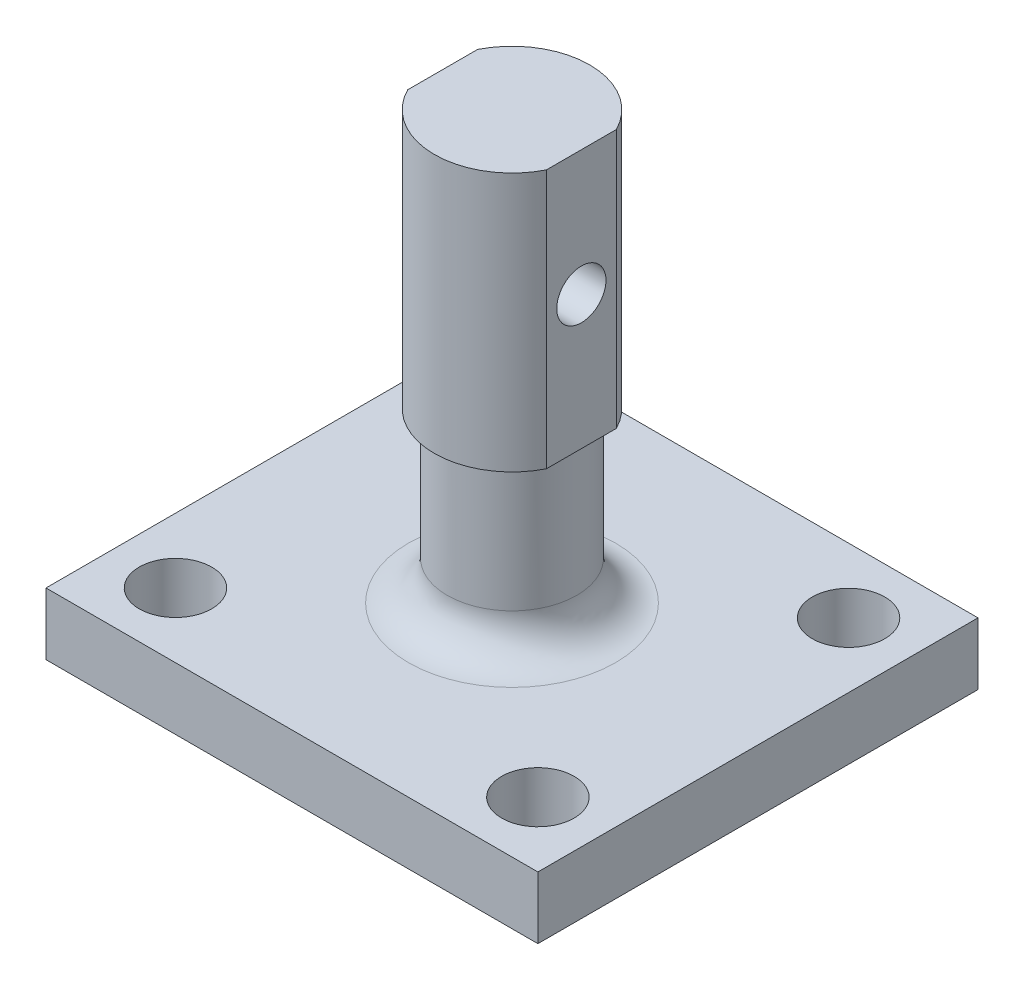
SolidWorks part; units mm, degrees
ref_plane "Front Plane" through (0, 0, 0) normal (0, 0, 1) x (1, 0, 0)
ref_plane "Top Plane" through (0, 0, 0) normal (0, 1, 0) x (1, 0, 0)
ref_plane "Right Plane" through (0, 0, 0) normal (1, 0, 0) x (0, 0, -1)
sketch "Sketch1" plane through (0, 0, 0) normal (0, 1, 0) x (1, 0, 0)
  line L1 (-4.75, 4.25) -> (4.75, 4.25)
  line L2 (-4.75, 4.25) -> (-4.75, -4.25)
  line L3 (-4.75, -4.25) -> (4.75, -4.25)
  line L4 (4.75, 4.25) -> (4.75, -4.25)
  line L5 (-4.75, 4.25) -> (4.75, -4.25) construction
  line L6 (-4.75, -4.25) -> (4.75, 4.25) construction
  point P0 (0, 0)
  dimension "D1" = 8.5
  dimension "D2" = 9.5
extrude "Boss-Extrude1" add sketch "Sketch1" along normal blind 1.2
sketch "Sketch2" plane through (0, 1.2, 0) normal (0, 1, 0) x (1, 0, 0)
  line L0 (0, 0) -> (-4.75, 0) construction
  line L1 (0, 0) -> (0, -4.25) construction
  line L2 (-4.75, 4.25) -> (-4.75, -4.25) construction
  line L3 (-4.75, -4.25) -> (4.75, -4.25) construction
  circle A4 centre (-3.5, -3) radius 0.7
  circle A5 centre (-3.5, 3) radius 0.7
  circle A6 centre (3.5, 3) radius 0.7
  circle A7 centre (3.5, -3) radius 0.7
  dimension "D3" = 1.4
  dimension "D1" = 7
  dimension "D2" = 6
extrude "Cut-Extrude1" cut sketch "Sketch2" against normal through all both and the other way through all
sketch "Sketch8" plane through (0, 0, 0) normal (0, 0, 1) x (1, 0, 0)
  line L0 (0, 1.2) -> (0, 4.0526)
  line L1 (4.75, 1.2) -> (-4.75, 1.2) construction
  line L2 (0, -0.66) -> (0, 0.66) construction
  line L3 (5.32, 8.6361) -> (5.32, 11.7767)
  line L4 (4.75, 1.2) -> (4.75, 0) construction
  spline S0 degree 3 poles (5.32, 8.6361) (5.32, 6.9802) (3.7001, 6.877) (1.2599, 5.7161) (0, 4.8321) (0, 4.0526) knots 0 0 0 0 0.545887 0.645887 1 1 1 1
  dimension "D1" = 0.57
sketch "Sketch9" plane through (0, 1.2, 0) normal (0, 1, 0) x (1, 0, 0)
  circle A0 centre (0, 0) radius 1.5
  dimension "D1" = 3
sketch "Sketch5" plane through (0, 1.2, 0) normal (0, 1, 0) x (1, 0, 0)
  circle A0 centre (0, 0) radius 1.25
  dimension "D1" = 2.5
extrude "Boss-Extrude2" add sketch "Sketch5" along normal blind 3.25
hole_wizard "Tap Drill for M2.5x0.45 Tap1" [suppressed] positions "3DSketch1" profile "Sketch6" hole size "M2.5x0.45" standard "ANSI Metric"
sketch3d "3DSketch1"
  line L0 (0, 1.7, 0) -> (0, 1.2, 0) construction
  point P0 (0, 1.7, 0)
sketch "Sketch6" plane through (0, 1.7, 0) normal (1, 0, 0) x (0, 0, 1)
  line L0 (0, 0) -> (0, 1.7)
  line L1 (0, 1.7) -> (1.025, 1.7)
  line L2 (1.025, 1.7) -> (1.025, 0)
  line L5 (1.025, 0) -> (0, 0)
  line L11 (0, -6.35) -> (0, 107.95) construction
  dimension "Thru Hole Dia." = 2.05
  dimension "Thru Hole Depth" = 1.7
fillet "Fillet1" radius 0.75 1 edges at (0, 1.2, 1.25)
sketch "Sketch36" plane through (0, 4.45, 0) normal (0, 1, 0) x (1, 0, 0)
  line L1 (0.7875, -1.364) -> (1.575, 0)
  line L2 (1.575, 0) -> (0.7875, 1.364)
  line L3 (0.7875, 1.364) -> (-0.7875, 1.364)
  line L4 (-0.7875, 1.364) -> (-1.575, 0)
  line L5 (-1.575, 0) -> (-0.7875, -1.364)
  line L6 (-0.7875, -1.364) -> (0.7875, -1.364)
  line L7 (0, 0) -> (5.32, 0) construction
  circle A0 centre (0, 0) radius 1.575 construction
  circle A1 centre (0, 0) radius 1.364 construction
  dimension "D1" = 3.15
sketch "Sketch37" plane through (0, 4.45, 0) normal (0, 1, 0) x (1, 0, 0)
  circle A0 centre (0, 0) radius 1.5
  dimension "D1" = 3
extrude "Boss-Extrude3" add sketch "Sketch37" along normal blind 5
fillet "Fillet2" [suppressed] radius 0.5
sketch "Sketch39" plane through (0, 9.45, 0) normal (0, 1, 0) x (1, 0, 0)
  line L5 (-5.1975, 0) -> (5.1975, 0) construction
  line L6 (2.75, -0.625) -> (0.25, -0.625)
  line L7 (2.75, -0.625) -> (2.75, 0.625)
  line L8 (2.75, 0.625) -> (0.25, 0.625)
  line L9 (0.25, -0.625) -> (0.25, 0.625)
  line L10 (2.75, -0.625) -> (0.25, 0.625) construction
  line L11 (2.75, 0.625) -> (0.25, -0.625) construction
  circle A2 centre (0, 0) radius 1.5 construction
  point P0 (1.5, 0)
  dimension "D1" = 1.25
  dimension "D2" = 1.25
extrude "Cut-Extrude2" [suppressed] cut sketch "Sketch39" against normal blind 9
sketch "Sketch40" plane through (0, 9.45, 0) normal (0, 1, 0) x (1, 0, 0)
  line L0 (-1.3395, 0.675) -> (-1.3395, -0.675)
  line L1 (1.3395, 0.675) -> (1.3395, -0.675)
  line L2 (-1.3395, 0.675) -> (1.3395, 0.675) construction
  line L3 (-1.3395, -0.675) -> (1.3395, -0.675) construction
  circle A0 centre (0, 0) radius 1.5 construction
  arc A1 (1.3395, 0.675) -> (1.3395, -0.675) centre (0, 0) cw
  arc A2 (-1.3395, 0.675) -> (-1.3395, -0.675) centre (0, 0) ccw
  dimension "D1" = 1.35
extrude "Cut-Extrude3" cut sketch "Sketch40" against normal blind 6
sketch "Sketch41" plane through (1.3395, 0, 0) normal (1, 0, 0) x (0, 0, -1)
  line L0 (0, 5.1975) -> (0, -5.1975) construction
  line L1 (0.675, 9.45) -> (-0.675, 9.45) construction
  circle A0 centre (0, 7.03) radius 0.475
  dimension "D1" = 2.42
  dimension "D2" = 0.95
extrude "Cut-Extrude4" cut sketch "Sketch41" against normal blind 10
hole_wizard "Tap Drill for M2.5x0.45 Tap2" [suppressed] positions "Sketch43" profile "Sketch44" hole size "M2.5x0.45" standard "ANSI Metric"
sketch "Sketch43" plane through (0, 3, 0) normal (0, 1, 0) x (1, 0, 0)
  point P0 (0, 0)
sketch "Sketch44" plane through (0, 3, 0) normal (1, 0, 0) x (0, 0, 1)
  line L0 (0, 0) -> (0, 2.6159)
  line L1 (0, 2.6159) -> (1.025, 2)
  line L2 (1.025, 2) -> (1.025, 0)
  line L5 (1.025, 0) -> (0, 0)
  line L10 (0, 2.6159) -> (-1.025, 2) construction
  line L11 (0, -6.35) -> (0, 107.95) construction
  dimension "Hole Dia." = 2.05
  dimension "Hole Depth" = 3
  dimension "Drill Angle" = 118
sketch "Sketch42" [suppressed] plane through (0, 3, 0) normal (0, 1, 0) x (1, 0, 0)
  circle A0 centre (0, 0) radius 0.5
  dimension "D1" = 1
extrude "Cut-Extrude5" [suppressed] cut sketch "Sketch42" against normal through all
